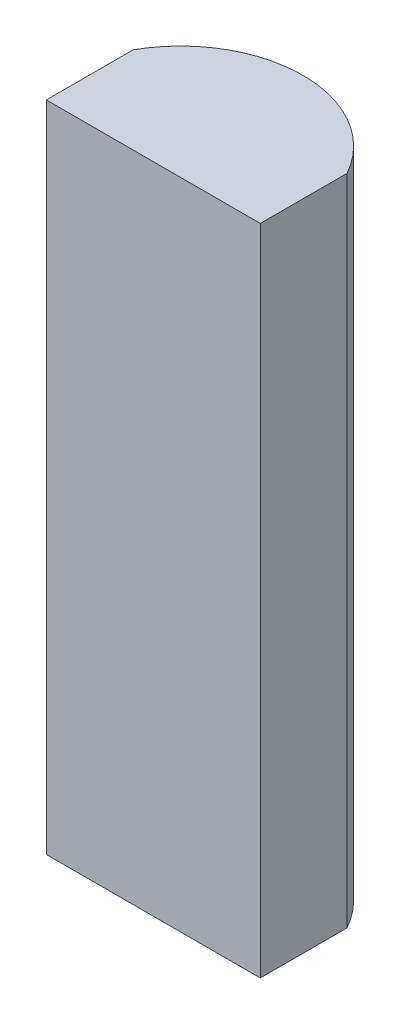
SolidWorks part; units mm, degrees
ref_plane "Front Plane" through (0, 0, 0) normal (0, 0, 1) x (1, 0, 0)
ref_plane "Top Plane" through (0, 0, 0) normal (0, 1, 0) x (1, 0, 0)
ref_plane "Right Plane" through (0, 0, 0) normal (1, 0, 0) x (0, 0, -1)
sketch "Sketch1" plane through (0, 0, 0) normal (0, 1, 0) x (1, 0, 0)
  line L6 (-62.2, -15.8) -> (62.2, -15.8)
  line L7 (62.2, -15.8) -> (62.2, 34.6497)
  line L8 (-62.2, 34.6497) -> (-62.2, -15.8)
  line L9 (0, 86.5533) -> (0, -102.8225) construction
  arc A2 (62.2, 34.6497) -> (-62.2, 34.6497) centre (0, 0) ccw
  dimension "D3" = 124.4
  dimension "D1" = 71.2
  dimension "D4" = 50.4497
extrude "Boss-Extrude1" add sketch "Sketch1" along normal blind 380
